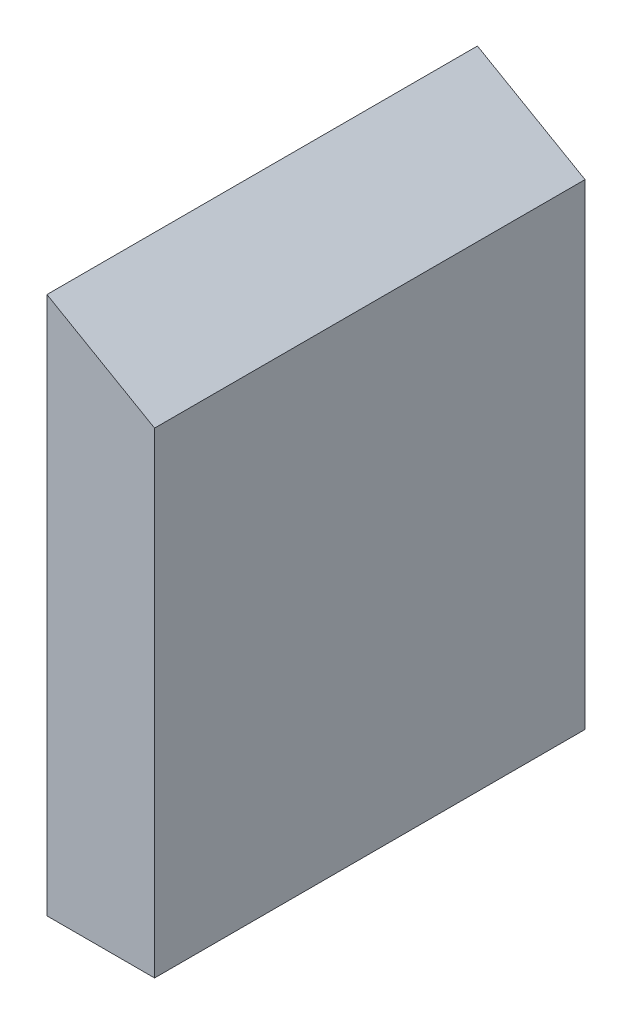
SolidWorks part; units mm, degrees
ref_plane "Front Plane" through (0, 0, 0) normal (0, 0, 1) x (1, 0, 0)
ref_plane "Top Plane" through (0, 0, 0) normal (0, 1, 0) x (1, 0, 0)
ref_plane "Right Plane" through (0, 0, 0) normal (1, 0, 0) x (0, 0, -1)
sketch "Sketch1" plane through (0, 0, 0) normal (0, 0, 1) x (1, 0, 0)
  line L0 (0, 0) -> (0, 50)
  line L1 (0, 0) -> (10, 0)
  line L2 (10, 0) -> (10, 44.25)
  line L3 (0, 50) -> (10, 44.25)
  dimension "D1" = 50
  dimension "D2" = 10
  dimension "D3" = 44.25
  dimension "D4" = 11.5353
extrude "Boss-Extrude1" add sketch "Sketch1" along normal blind 40 contours L2 L3 L0 L1
